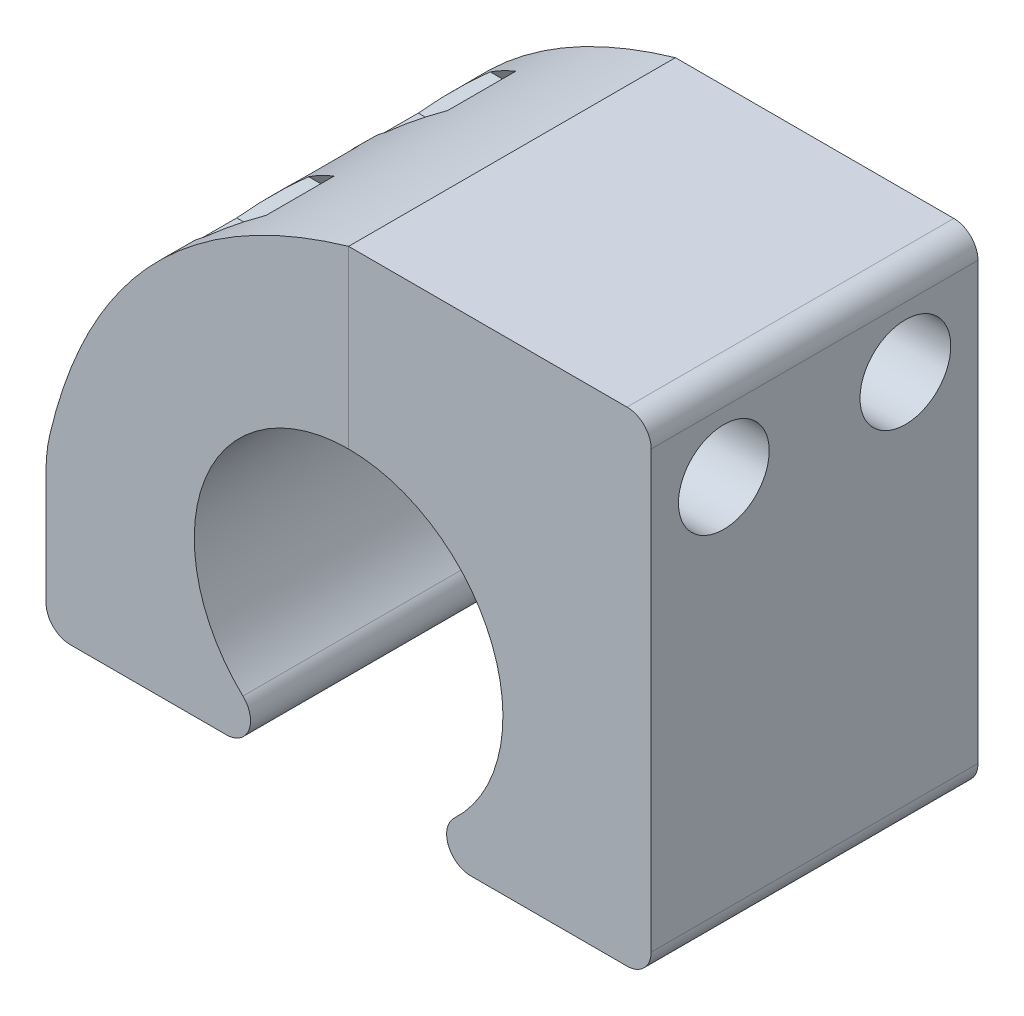
SolidWorks part; units mm, degrees
ref_plane "Front Plane" through (0, 0, 0) normal (0, 0, 1) x (1, 0, 0)
ref_plane "Top Plane" through (0, 0, 0) normal (0, 1, 0) x (1, 0, 0)
ref_plane "Right Plane" through (0, 0, 0) normal (1, 0, 0) x (0, 0, -1)
sketch "Sketch1" plane through (0, 0, 0) normal (0, 0, 1) x (1, 0, 0)
  line L0 (10.0995, -12.75) -> (25, -12.75)
  line L1 (-25, -12.75) -> (-10.0995, -12.75)
  line L2 (-25, -12.75) -> (-25, 27.25)
  line L3 (-25, 27.25) -> (25, 27.25)
  line L4 (25, -12.75) -> (25, 27.25)
  arc A0 (8.7301, -9.2924) -> (-8.7301, -9.2924) centre (0, 0) ccw
  arc A1 (8.7301, -9.2924) -> (10.0995, -12.75) centre (10.0995, -10.75) ccw
  arc A2 (-8.7301, -9.2924) -> (-10.0995, -12.75) centre (-10.0995, -10.75) cw
  point P4 (0, 27.25)
  point P9 (0, -12.75)
  dimension "D1" = 25.5
  dimension "D5" = 2
  dimension "D6" = 50
  dimension "D2" = 40
  dimension "D3" = 12.75
  dimension "D4" = 12.75
extrude "Boss-Extrude1" add sketch "Sketch1" along normal mid plane 27
sketch "Sketch2" plane through (0, 0, 13.5) normal (0, 0, 1) x (1, 0, 0)
  line L0 (0, 27.25) -> (0, 0)
  line L1 (25, 27.25) -> (-25, 27.25) construction
fillet "Fillet1" radius 2 3 edges at (25, -12.75, 0) (25, 27.25, 0) (-25, -12.75, 0)
split "Split1" trim tools "Sketch2" bodies to split 101 resulting bodies 102 103
sketch "Sketch3" plane through (25, 0, 0) normal (1, 0, 0) x (0, 0, -1)
  line L0 (-13.5, 27.25) -> (13.5, 27.25) construction
  line L1 (0, 0) -> (0, 23.0503) construction
  circle A0 centre (-7.5, 20.25) radius 3.75
  circle A1 centre (7.5, 20.25) radius 3.75
  point P2 (-6.3062, 20.25)
  point P8 (-6.7209, 20.25)
  dimension "D1" = 7.5
  dimension "D2" = 7
  dimension "D3" = 15
extrude "Cut-Extrude1" cut sketch "Sketch3" against normal offset from surface (10 mm away) 15 up to face at (0, 20, 0)
sketch "Sketch7" plane through (15, 0, 0) normal (1, 0, 0) x (0, 0, -1)
  line L0 (0, 0) -> (0, 5.8858) construction
  circle A0 centre (-7.5, 20.25) radius 2.25
  circle A1 centre (7.5, 20.25) radius 2.25
  dimension "D1" = 4.5
extrude "Cut-Extrude3" cut sketch "Sketch7" against normal up to next (15 mm away)
sketch "Sketch6" plane through (0, 0, 13.5) normal (0, 0, 1) x (1, 0, 0)
  line L0 (-25, 27.25) -> (-25, -10.75) construction
  line L1 (0, 27.25) -> (-25, 27.25) construction
  line L2 (-25, 27.25) -> (-25, 0)
  line L3 (0, 27.25) -> (-25, 27.25)
  spline S0 degree 2 poles (0, 27.25) (-20.6736, 21.2338) (-25, 0) knots 0 0 0 1 1 1
extrude "Cut-Extrude2" cut sketch "Sketch6" against normal up to next (27 mm away)
fillet "Fillet2" radius 12 1 edges at (-25, 0, 0)
sketch "Sketch8" plane through (0, 0, 0) normal (1, 0, 0) x (0, 0, -1)
  circle A0 centre (7.5, 20.25) radius 2.25 construction
  circle A1 centre (-7.5, 20.25) radius 2.25 construction
  circle A2 centre (7.5, 20.25) radius 2.25
  circle A3 centre (-7.5, 20.25) radius 2.25
extrude "Cut-Extrude4" cut sketch "Sketch8" along direction (1, 0, 0) on the side against the normal up to surface (25 mm away)
sketch "Sketch9" plane through (-25, 0, 0) normal (-1, 0, 0) x (0, 0, 1)
  line L0 (0, 0) -> (0, 7.3081) construction
  line L1 (-5.3349, 24) -> (-9.6651, 24)
  line L2 (-9.6651, 24) -> (-11.8301, 20.25)
  line L3 (-11.8301, 20.25) -> (-9.6651, 16.5)
  line L4 (-9.6651, 16.5) -> (-5.3349, 16.5)
  line L5 (-5.3349, 16.5) -> (-3.1699, 20.25)
  line L6 (-3.1699, 20.25) -> (-5.3349, 24)
  line L7 (3.1699, 20.25) -> (5.3349, 24)
  line L8 (5.3349, 16.5) -> (3.1699, 20.25)
  line L9 (9.6651, 16.5) -> (5.3349, 16.5)
  line L10 (11.8301, 20.25) -> (9.6651, 16.5)
  line L11 (9.6651, 24) -> (11.8301, 20.25)
  line L12 (5.3349, 24) -> (9.6651, 24)
  circle A0 centre (-7.5, 20.25) radius 3.75 construction
  circle A1 centre (7.5, 20.25) radius 3.75 construction
  point P10 (-7.5, 24)
  dimension "D1" = 7.5
extrude "Cut-Extrude5" cut sketch "Sketch9" against normal blind 15
sketch "Sketch10" plane through (0, -12.75, 0) normal (0, -1, 0) x (1, 0, 0)
  line L1 (0, -13.5) -> (0, 13.5) construction
  circle A0 centre (18.5, 0) radius 2.25 construction
  circle A1 centre (-18.5, 0) radius 2.25
  point P2 (16.757, 0)
  point P4 (0, 0)
  point P12 (0, 0)
  point P13 (18.9661, 0)
  dimension "D1" = 4.5
  dimension "D2" = 37
extrude "Cut-Extrude6" cut sketch "Sketch10" against normal blind 35
sketch "Sketch11" plane through (0, 27.25, 0) normal (0, 1, 0) x (1, 0, 0)
  line L1 (-14.75, -2.1651) -> (-14.75, 2.1651)
  line L2 (-14.75, 2.1651) -> (-18.5, 4.3301)
  line L3 (-18.5, 4.3301) -> (-22.25, 2.1651)
  line L4 (-22.25, 2.1651) -> (-22.25, -2.1651)
  line L5 (-22.25, -2.1651) -> (-18.5, -4.3301)
  line L6 (-18.5, -4.3301) -> (-14.75, -2.1651)
  circle A0 centre (-18.5, 0) radius 3.75 construction
  point P1 (0, 0)
  point P10 (-14.75, 0)
  dimension "D1" = 7.5
extrude "Cut-Extrude7" cut sketch "Sketch11" against normal blind 17
other "Save Bodies1"
